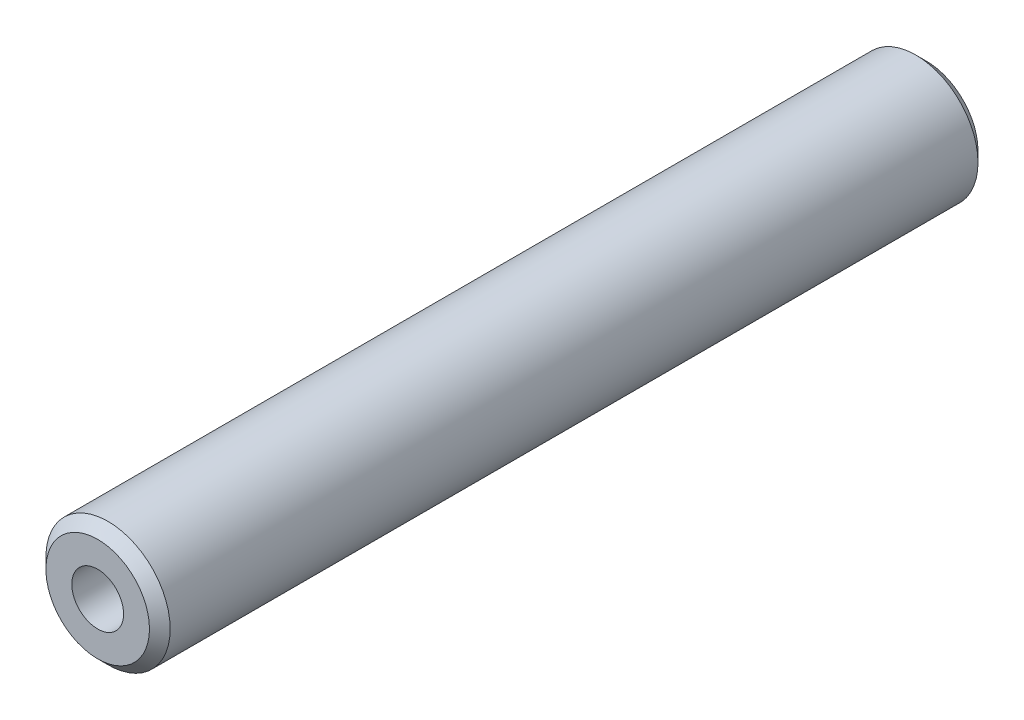
SolidWorks part; units mm, degrees
material "KS26"
ref_plane "正面" through (0, 0, 0) normal (0, 0, 1) x (1, 0, 0)
ref_plane "平面" through (0, 0, 0) normal (0, 1, 0) x (1, 0, 0)
ref_plane "右側面" through (0, 0, 0) normal (1, 0, 0) x (0, 0, -1)
sketch "ｽｹｯﾁ2" plane through (0, 0, 0) normal (0, 0, 1) x (1, 0, 0)
  circle A0 centre (0, 0) radius 3
  dimension "D1" = 6
extrude "ﾎﾞｽ - 押し出し1" add sketch "ｽｹｯﾁ2" along normal mid plane 40
hole_wizard "M3 ねじ穴1" positions "ｽｹｯﾁ3" profile "ｽｹｯﾁ4" tap size "M3" standard "JIS"
sketch "ｽｹｯﾁ3" plane through (0, 0, 20) normal (0, 0, 1) x (1, 0, 0)
  point P0 (0, 0)
sketch "ｽｹｯﾁ4" plane through (0, 0, 20) normal (1, 0, 0) x (0, -1, 0)
  line L0 (0, 0) -> (0, 9.2511)
  line L1 (0, 9.2511) -> (1.25, 8.5)
  line L2 (1.25, 8.5) -> (1.25, 0)
  line L5 (1.25, 0) -> (0, 0)
  line L10 (0, 9.2511) -> (-1.25, 8.5) construction
  line L11 (0, -6.35) -> (0, 107.95) construction
  dimension "ねじ下穴ﾄﾞﾘﾙ直径" = 2.5
  dimension "ねじ下穴ﾄﾞﾘﾙの深さ" = 8.5
  dimension "ﾄﾞﾘﾙ角度" = 118
cosmetic thread "穴のねじ山1" parameters "D1"=6, "D2"=3
mirror "ﾐﾗｰ1" about plane through (0, 0, 0) normal (0, 0, 1) of "M3 ねじ穴1"
chamfer "面取り1" distance 0.5 angle 45 2 edges at (3, 0, -20) (3, 0, 20)
